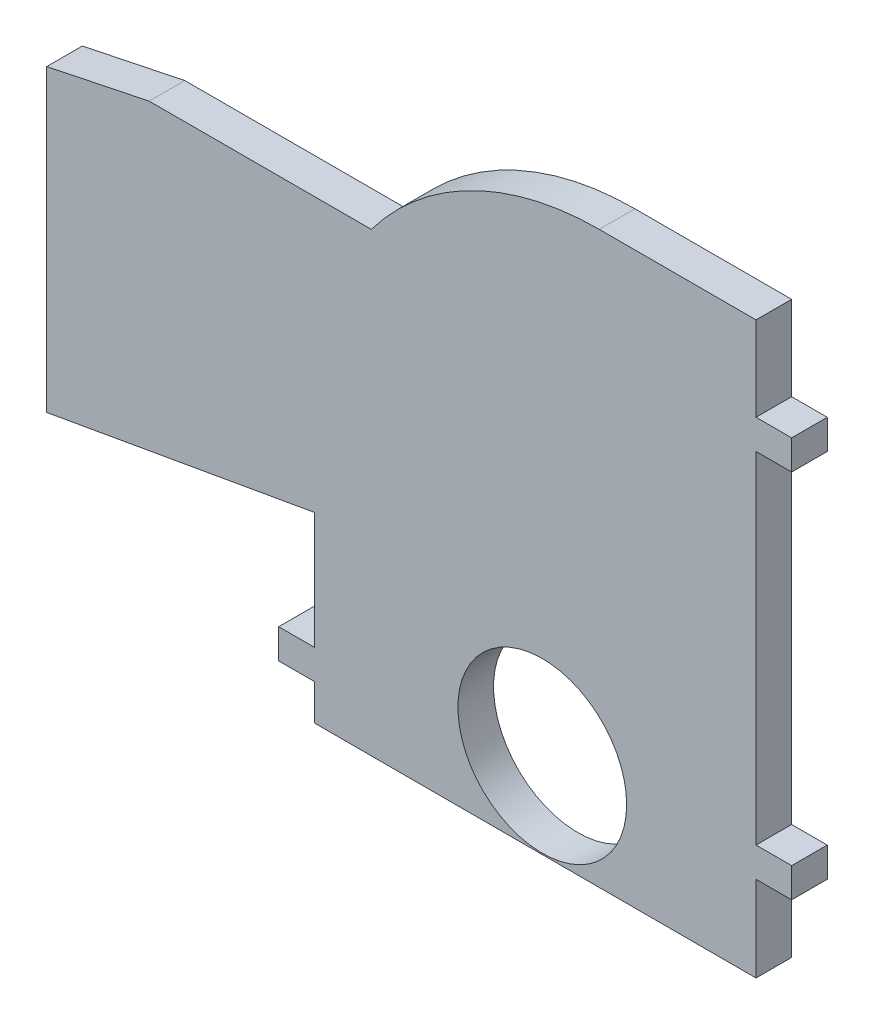
SolidWorks part; units mm, degrees
material "Balsa"
ref_plane "Front Plane" through (0, 0, 0) normal (0, 0, 1) x (1, 0, 0)
ref_plane "Top Plane" through (0, 0, 0) normal (0, 1, 0) x (1, 0, 0)
ref_plane "Right Plane" through (0, 0, 0) normal (1, 0, 0) x (0, 0, -1)
sketch "Sketch1" plane through (0, 0, 0) normal (0, 0, 1) x (1, 0, 0)
  line L0 (0, -1000.1535) -> (0, 48999.8465) construction
  line L1 (-7.62, 16.51) -> (-17.5195, 16.51)
  line L2 (-1000, 0) -> (49000, 0) construction
  line L3 (9.525, 16.51) -> (11.1125, 16.51)
  line L4 (2.54, 21.59) -> (9.525, 21.59)
  line L5 (-10.16, 8.89) -> (-10.16, -3.81)
  line L6 (-10.16, -3.81) -> (9.525, -3.81)
  line L7 (9.525, 21.59) -> (9.525, -3.81)
  line L8 (-11.7475, -2.2098) -> (-10.16, -2.2098)
  line L9 (-11.7475, -2.2098) -> (-11.7475, -0.889)
  line L10 (-11.7475, -0.889) -> (-10.16, -0.889)
  line L11 (-10.16, -2.2098) -> (-10.16, -0.889)
  line L12 (9.525, 0) -> (11.1125, 0)
  line L13 (9.525, 0) -> (9.525, 1.3208)
  line L14 (9.525, 1.3208) -> (11.1125, 1.3208)
  line L15 (11.1125, 0) -> (11.1125, 1.3208)
  line L16 (9.525, 16.51) -> (9.525, 17.8308)
  line L17 (9.525, 17.8308) -> (11.1125, 17.8308)
  line L18 (11.1125, 16.51) -> (11.1125, 17.8308)
  line L20 (-22.0849, 2.212) -> (-10.16, 4.318)
  line L21 (-22.0849, 4.699) -> (-22.0849, 2.212)
  line L22 (-22.0849, 13.081) -> (-22.0849, 4.699)
  line L26 (-17.5195, 16.51) -> (-22.0849, 15.5612)
  line L27 (-22.0849, 13.081) -> (-22.0849, 15.5612)
  circle A0 centre (0, 0) radius 3.7592
  arc A3 (2.54, 21.59) -> (-10.16, 8.89) centre (2.54, 8.89) ccw
  dimension "D1" = 7.5184
  dimension "D4" = 3.81
  dimension "D3" = 7.3595
  dimension "D5" = 0.9488
  dimension "D9" = 12.7
  dimension "D10" = 1.5875
  dimension "D2" = 25.4
  dimension "D6" = 9.525
  dimension "D7" = 2.106
  dimension "D8" = 19.685
  dimension "D11" = 5.207
  dimension "D12" = 1.3208
  dimension "D13" = 1.3208
  dimension "D14" = 1.5875
  dimension "D15" = 2
extrude "Boss-Extrude1" add sketch "Sketch1" along normal blind 1.5875
move or copy body "Body-Move/Copy1" [suppressed] bodies to move or copy 101
